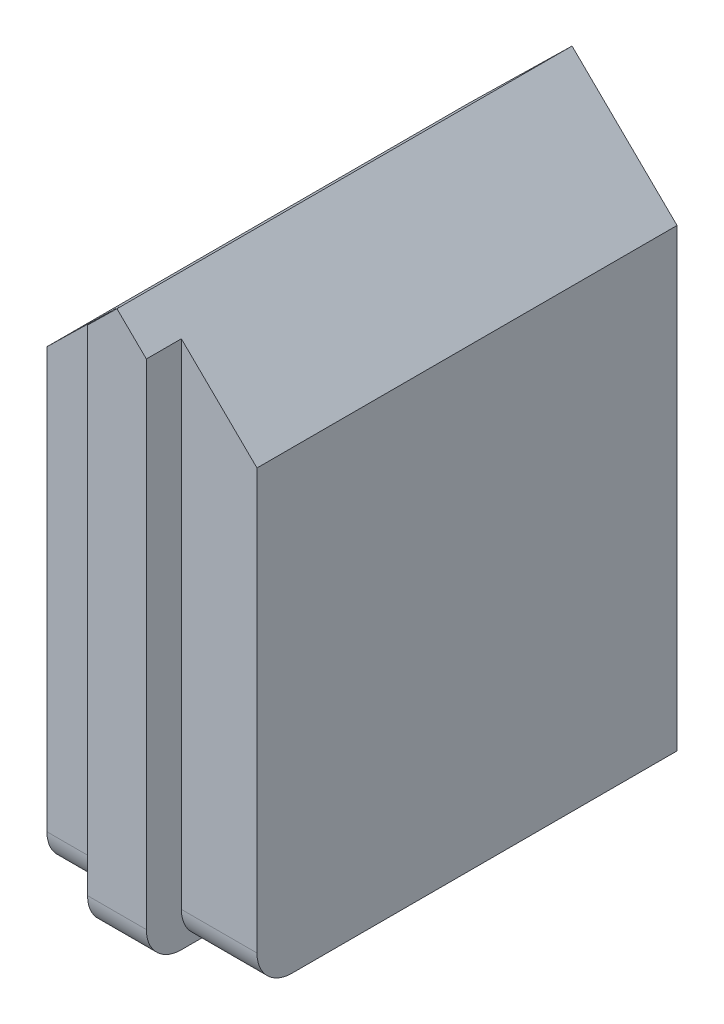
SolidWorks part; units mm, degrees
ref_plane "Plan de face" through (0, 0, 0) normal (0, 0, 1) x (1, 0, 0)
ref_plane "Plan de dessus" through (0, 0, 0) normal (0, 1, 0) x (1, 0, 0)
ref_plane "Plan de droite" through (0, 0, 0) normal (1, 0, 0) x (0, 0, -1)
sketch "Esquisse1" plane through (0, 0, 0) normal (0, 0, 1) x (1, 0, 0)
  line L0 (0, 0) -> (0, 13)
  line L1 (0, 13) -> (3, 15.9394)
  line L2 (3, 15.9394) -> (6, 13)
  line L3 (6, 13) -> (6, 0)
  line L4 (6, 0) -> (0, 0)
  dimension "D1" = 6
  dimension "D2" = 13
  dimension "D3" = 4.2
extrude "Extrusion1" add sketch "Esquisse1" along normal blind 12
ref_plane "Plan1" through (3, 15.9394, 12) normal (-0.7143, -0.6999, 0) x (0.6999, -0.7143, 0)
sketch "Esquisse3" plane through (0, 0, 12) normal (0, 0, 1) x (1, 0, 0)
  line L0 (2.16, 15.1164) -> (2.16, 0)
  line L1 (3, 15.9394) -> (0, 13) construction
  line L2 (0, 0) -> (6, 0) construction
  line L3 (2.16, 0) -> (3.84, 0)
  line L4 (3.84, 0) -> (3.84, 15.1164)
  line L5 (6, 13) -> (3, 15.9394) construction
  line L6 (3.84, 15.1164) -> (3, 15.9394)
  line L7 (3, 15.9394) -> (2.16, 15.1164)
extrude "Extrusion2" add sketch "Esquisse3" along normal blind 1
fillet "Congé3" radius 1 1 edges
fillet "Congé4" radius 1 2 edges
fillet "Congé5" radius 1 3 edges at (3, 0, 13)
